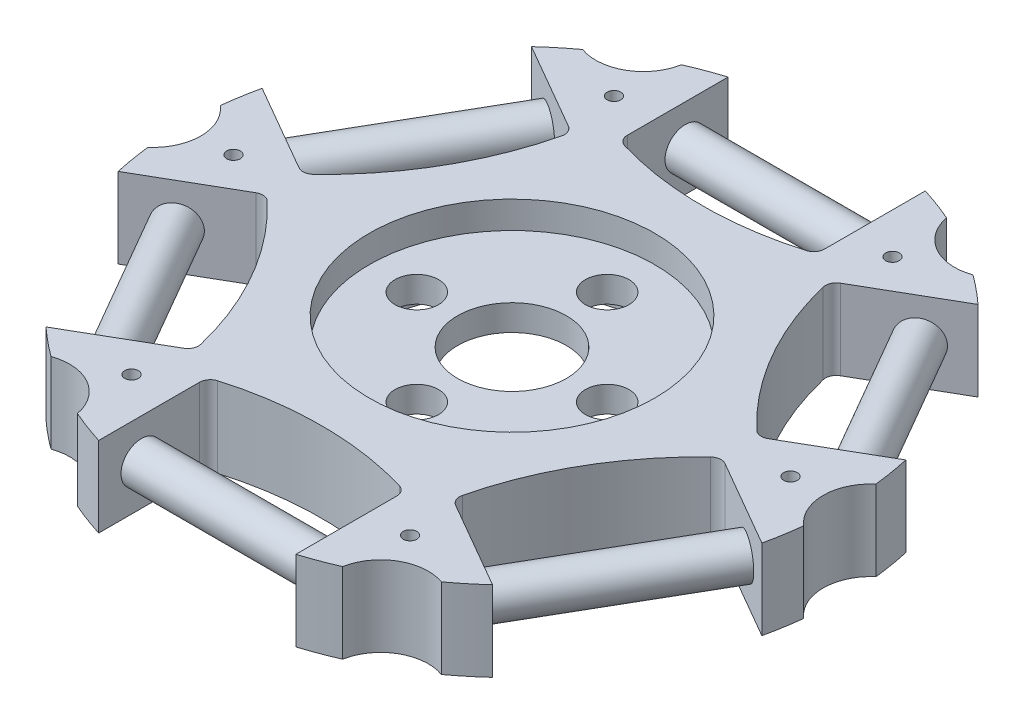
SolidWorks part; units mm, degrees
material "1060 合金"
ref_plane "前视基准面" through (0, 0, 0) normal (0, 0, 1) x (1, 0, 0)
ref_plane "上视基准面" through (0, 0, 0) normal (0, 1, 0) x (1, 0, 0)
ref_plane "右视基准面" through (0, 0, 0) normal (1, 0, 0) x (0, 0, -1)
ref_plane "基准面4" through (0, 0, 0) normal (0, 0, -1) x (-1, 0, 0)
sketch "草图1" plane through (0, 0, 0) normal (0, 0, -1) x (-1, 0, 0)
  line L0 (-24.25, -3) -> (0, -3)
  line L1 (0, -3) -> (0, 2.9)
  line L2 (0, 2.9) -> (-24.25, 2.9)
  line L3 (-24.25, 2.9) -> (-24.25, -3)
  line L4 (0, -3) -> (0, 2.9) construction
revolve "旋转1" add sketch "草图1" angle 360 about L4
sketch "草图2" plane through (0, 2.9, 0) normal (0, 1, 0) x (-1, 0, 0)
  line L0 (-7.25, 23.1409) -> (-7.25, 15.1409)
  line L1 (7.25, 15.1409) -> (7.25, 23.1409)
  arc A0 (7.25, 23.1409) -> (-7.25, 23.1409) centre (0, 0) ccw
  arc A1 (-7.25, 15.1409) -> (7.25, 15.1409) centre (0, 37.6065) ccw
extrude "切除-拉伸1" cut sketch "草图2" against normal through all
sketch "草图3" plane through (0, 2.9, 0) normal (0, 1, 0) x (-1, 0, 0)
  arc A0 (14.3544, 19.5451) -> (9.7494, 22.2039) centre (0, 0) ccw
  arc A1 (9.7494, 22.2039) -> (14.3544, 19.5451) centre (13.19, 22.8458) ccw
extrude "切除-拉伸2" cut sketch "草图3" against normal through all
sketch "草图4" plane through (0, 2.9, 0) normal (0, 1, 0) x (-1, 0, 0)
  line L0 (16.4156, 17.8491) -> (9.4874, 13.8491)
  line L1 (16.7374, 1.2918) -> (23.6656, 5.2918)
  arc A0 (23.6656, 5.2918) -> (16.4156, 17.8491) centre (0, 0) ccw
  arc A1 (9.4874, 13.8491) -> (16.7374, 1.2918) centre (32.5682, 18.8033) ccw
extrude "切除-拉伸3" cut sketch "草图4" against normal through all
sketch "草图5" plane through (0, 2.9, 0) normal (0, 1, 0) x (-1, 0, 0)
  arc A0 (24.1038, -2.6587) -> (24.1038, 2.6587) centre (0, 0) ccw
  arc A1 (24.1038, 2.6587) -> (24.1038, -2.6587) centre (26.38, 0) ccw
extrude "切除-拉伸4" cut sketch "草图5" against normal through all
sketch "草图6" plane through (0, 2.9, 0) normal (0, 1, 0) x (-1, 0, 0)
  line L0 (23.6656, -5.2918) -> (16.7374, -1.2918)
  line L1 (9.4874, -13.8491) -> (16.4156, -17.8491)
  arc A0 (16.4156, -17.8491) -> (23.6656, -5.2918) centre (0, 0) ccw
  arc A1 (16.7374, -1.2918) -> (9.4874, -13.8491) centre (32.5682, -18.8033) ccw
extrude "切除-拉伸5" cut sketch "草图6" against normal through all
sketch "草图7" plane through (0, 2.9, 0) normal (0, 1, 0) x (-1, 0, 0)
  arc A0 (9.7494, -22.2039) -> (14.3544, -19.5451) centre (0, 0) ccw
  arc A1 (14.3544, -19.5451) -> (9.7494, -22.2039) centre (13.19, -22.8458) ccw
extrude "切除-拉伸6" cut sketch "草图7" against normal through all
sketch "草图8" plane through (0, 2.9, 0) normal (0, 1, 0) x (-1, 0, 0)
  line L0 (7.25, -23.1409) -> (7.25, -15.1409)
  line L1 (-7.25, -15.1409) -> (-7.25, -23.1409)
  arc A0 (-7.25, -23.1409) -> (7.25, -23.1409) centre (0, 0) ccw
  arc A1 (7.25, -15.1409) -> (-7.25, -15.1409) centre (0, -37.6065) ccw
extrude "切除-拉伸7" cut sketch "草图8" against normal through all
sketch "草图9" plane through (0, 2.9, 0) normal (0, 1, 0) x (-1, 0, 0)
  arc A0 (-14.3544, -19.5451) -> (-9.7494, -22.2039) centre (0, 0) ccw
  arc A1 (-9.7494, -22.2039) -> (-14.3544, -19.5451) centre (-13.19, -22.8458) ccw
extrude "切除-拉伸8" cut sketch "草图9" against normal through all
sketch "草图10" plane through (0, 2.9, 0) normal (0, 1, 0) x (-1, 0, 0)
  line L0 (-16.4156, -17.8491) -> (-9.4874, -13.8491)
  line L1 (-16.7374, -1.2918) -> (-23.6656, -5.2918)
  arc A0 (-23.6656, -5.2918) -> (-16.4156, -17.8491) centre (0, 0) ccw
  arc A1 (-9.4874, -13.8491) -> (-16.7374, -1.2918) centre (-32.5682, -18.8033) ccw
extrude "切除-拉伸9" cut sketch "草图10" against normal through all
sketch "草图11" plane through (0, 2.9, 0) normal (0, 1, 0) x (-1, 0, 0)
  arc A0 (-24.1038, 2.6587) -> (-24.1038, -2.6587) centre (0, 0) ccw
  arc A1 (-24.1038, -2.6587) -> (-24.1038, 2.6587) centre (-26.38, 0) ccw
extrude "切除-拉伸10" cut sketch "草图11" against normal through all
sketch "草图12" plane through (0, 2.9, 0) normal (0, 1, 0) x (-1, 0, 0)
  line L0 (-23.6656, 5.2918) -> (-16.7374, 1.2918)
  line L1 (-9.4874, 13.8491) -> (-16.4156, 17.8491)
  arc A0 (-16.4156, 17.8491) -> (-23.6656, 5.2918) centre (0, 0) ccw
  arc A1 (-16.7374, 1.2918) -> (-9.4874, 13.8491) centre (-32.5682, 18.8033) ccw
extrude "切除-拉伸11" cut sketch "草图12" against normal through all
sketch "草图13" plane through (0, 2.9, 0) normal (0, 1, 0) x (-1, 0, 0)
  arc A0 (-9.7494, 22.2039) -> (-14.3544, 19.5451) centre (0, 0) ccw
  arc A1 (-14.3544, 19.5451) -> (-9.7494, 22.2039) centre (-13.19, 22.8458) ccw
extrude "切除-拉伸12" cut sketch "草图13" against normal through all
sketch "草图14" plane through (0, 0, 0) normal (0, 0, 1) x (1, 0, 0)
  line L0 (10.5, 2.9) -> (0, 2.9)
  line L1 (0, 2.9) -> (0, -3)
  line L2 (0, -3) -> (10.5, -3)
  line L3 (10.5, -3) -> (10.5, -1)
  line L4 (10.5, -1) -> (4, -1)
  line L5 (4, -1) -> (4, 0.9)
  line L6 (4, 0.9) -> (10.5, 0.9)
  line L7 (10.5, 0.9) -> (10.5, 2.9)
  line L8 (0, 2.9) -> (0, -3) construction
  dimension "D1" = 2
  dimension "D2" = 2
  dimension "D3" = 5.9
revolve "切除-旋转1" cut sketch "草图14" angle 360 about L8
ref_plane "基准面5" through (0, 0, 20) normal (0, 0, -1) x (-1, 0, 0)
sketch "草图15" plane through (0, 0, 20) normal (0, 0, -1) x (-1, 0, 0)
  line L0 (-7.25, 1.45) -> (-7.25, -0.05)
  line L1 (-7.25, -0.05) -> (7.25, -0.05)
  line L2 (7.25, -0.05) -> (7.25, 1.45)
  line L3 (7.25, 1.45) -> (-7.25, 1.45)
  line L4 (-7.25, -0.05) -> (7.25, -0.05) construction
  line L5 (7.25, 2.9) -> (-7.25, 2.9) construction
  dimension "D1" = 1.5
  dimension "D2" = 2.95
revolve "旋转2" add sketch "草图15" angle 360 about L4
ref_plane "基准面6" through (0, 0, 0) normal (0, -1, 0) x (1, 0, 0)
hole_wizard "Ø3.2 (3.2) 直径孔1" positions "草图22" profile "草图21" hole size "Ø3.2" standard "ANSI Metric"
sketch "草图22" plane through (0, -1, 0) normal (0, -1, 0) x (-1, 0, 0)
  point P0 (0, 7)
  point P1 (0, -7)
  point P2 (-7, 0)
  point P3 (7, 0)
sketch "草图21" plane through (0, -1, -7) normal (1, 0, 0) x (0, 0, -1)
  line L0 (0, 0) -> (0, 3.9)
  line L1 (0, 3.9) -> (1.6, 3.9)
  line L2 (1.6, 3.9) -> (1.6, 0)
  line L5 (1.6, 0) -> (0, 0)
  line L11 (0, -6.35) -> (0, 107.95) construction
  dimension "通孔孔直径" = 3.2
  dimension "通孔孔深度" = 3.9
fillet "圆角1" radius 0.8 12 edges at (-16.7374, -0.05, -1.2918) (7.25, -0.05, 15.1409) (-9.4874, -0.05, 13.8491) (16.7374, -0.05, 1.2918) (-9.4874, -0.05, -13.8491) (16.7374, -0.05, -1.2918) (-16.7374, -0.05, 1.2918) (9.4874, -0.05, -13.8491) (-7.25, -0.05, 15.1409) (7.25, -0.05, -15.1409) (9.4874, -0.05, 13.8491) (-7.25, -0.05, -15.1409)
sketch "草图23" plane through (0, -3, 0) normal (0, -1, 0) x (1, 0, 0)
  circle A3 centre (20.48, 0) radius 0.5
extrude "切除-拉伸13" cut sketch "草图23" against normal blind 10
pattern_circular "阵列(圆周)1" count 6 over 360 about axis through (0, 0, 0) along (0, 1, 0) of "切除-拉伸13"
pattern_circular "阵列(圆周)2" count 6 over 360 about axis through (0, 2.9, 0) along (0, -1, 0) of "旋转2"
